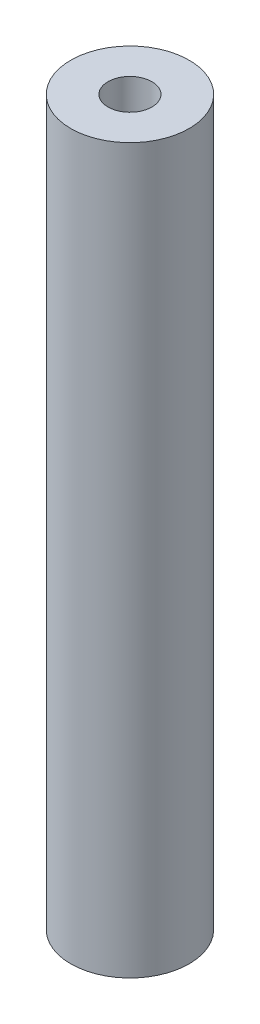
SolidWorks part; units mm, degrees
material "ABS"
ref_plane "Front Plane" through (0, 0, 0) normal (0, 0, 1) x (1, 0, 0)
ref_plane "Top Plane" through (0, 0, 0) normal (0, 1, 0) x (1, 0, 0)
ref_plane "Right Plane" through (0, 0, 0) normal (1, 0, 0) x (0, 0, -1)
sketch "Sketch1" plane through (0, 0, 0) normal (0, 1, 0) x (1, 0, 0)
  circle A0 centre (0, 0) radius 2.1209
  circle A1 centre (0, 0) radius 5.715
  dimension "D1" = 4.2418
  dimension "D2" = 11.43
extrude "Boss-Extrude1" add sketch "Sketch1" along normal blind 69.8246
